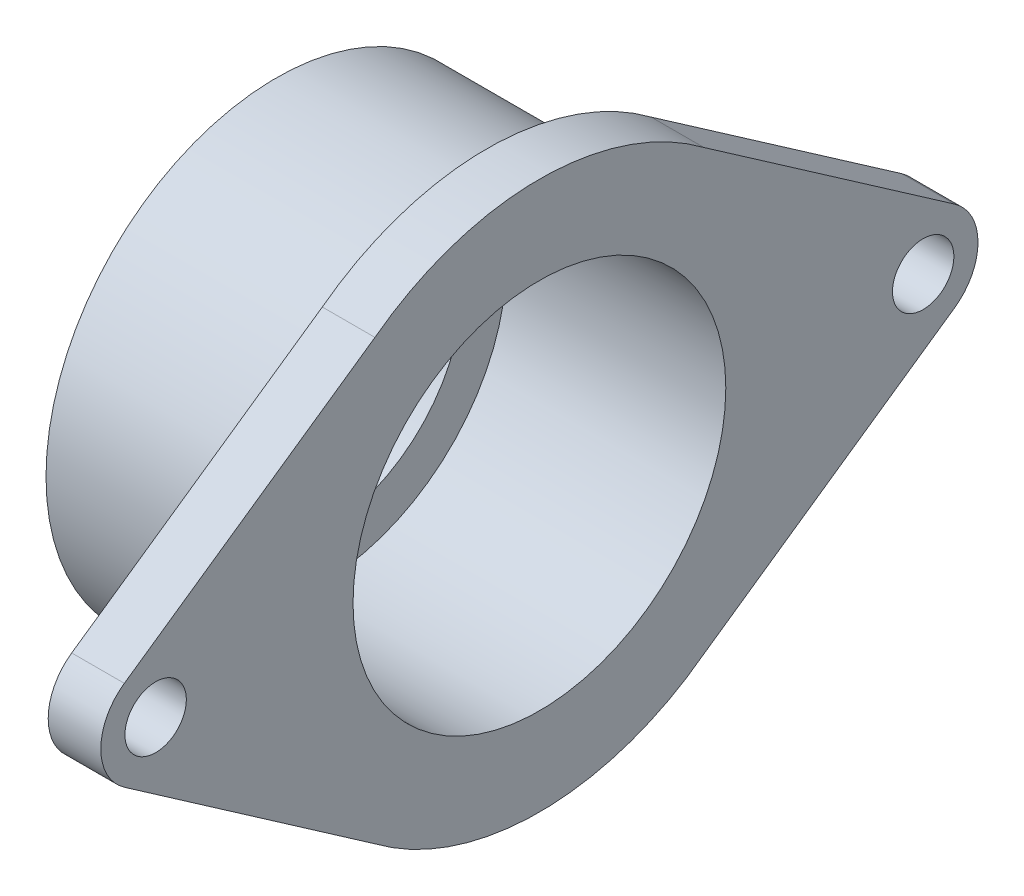
SolidWorks part; units mm, degrees
material "ASTM A36 Steel"
ref_plane "Front Plane" through (0, 0, 0) normal (0, 0, 1) x (1, 0, 0)
ref_plane "Top Plane" through (0, 0, 0) normal (0, 1, 0) x (1, 0, 0)
ref_plane "Right Plane" through (0, 0, 0) normal (1, 0, 0) x (0, 0, -1)
sketch "Sketch1" plane through (0, 0, 0) normal (0, 0, 1) x (1, 0, 0)
  line L0 (6.4952, 8.7781) -> (-53.5048, 8.7781)
  line L1 (-53.5048, 8.7781) -> (-53.5048, -11.2219)
  line L2 (-53.5048, -11.2219) -> (-43.5048, -11.2219)
  line L3 (-43.5048, -11.2219) -> (-43.5048, -1.2219)
  line L4 (-43.5048, -1.2219) -> (6.4952, -1.2219)
  line L5 (6.4952, -1.2219) -> (6.4952, 8.7781)
  line L6 (-50.0643, -43.7219) -> (18.2315, -43.7219)
  dimension "D1" = 60
  dimension "D2" = 10
  dimension "D3" = 32.5
  dimension "D4" = 10
  dimension "D5" = 10
revolve "Revolve1" add sketch "Sketch1" angle 360 about L6
sketch "Sketch2" plane through (6.4952, 0, 0) normal (1, 0, 0) x (0, 0, -1)
  line L1 (-37.5, -93.7219) -> (-94.6371, -53.984)
  line L2 (-37.5, 6.2781) -> (-94.6371, -33.4597)
  line L4 (37.5, -93.7219) -> (94.6371, -53.984)
  line L5 (37.5, 6.2781) -> (94.6371, -33.4597)
  arc A1 (37.5, 6.2781) -> (-37.5, 6.2781) centre (0, -43.7219) ccw
  arc A2 (-94.6371, -33.4597) -> (-94.6371, -53.984) centre (-87.5, -43.7219) ccw
  arc A3 (94.6371, -53.984) -> (94.6371, -33.4597) centre (87.5, -43.7219) ccw
  arc A4 (-37.5, -93.7219) -> (37.5, -93.7219) centre (0, -43.7219) ccw
  circle A7 centre (0, -43.7219) radius 52.5
  dimension "D1" = 125
  dimension "D4" = 25
  dimension "25" = 25
extrude "Boss-Extrude1" add sketch "Sketch2" against normal blind 12
sketch "Sketch3" plane through (6.4952, 0, 0) normal (1, 0, 0) x (0, 0, -1)
  circle A0 centre (87.5, -43.7219) radius 7
  circle A1 centre (-87.5, -43.7219) radius 7
  dimension "D1" = 14
  dimension "D2" = 14
extrude "Cut-Extrude1" cut sketch "Sketch3" against normal through all both and the other way through all
